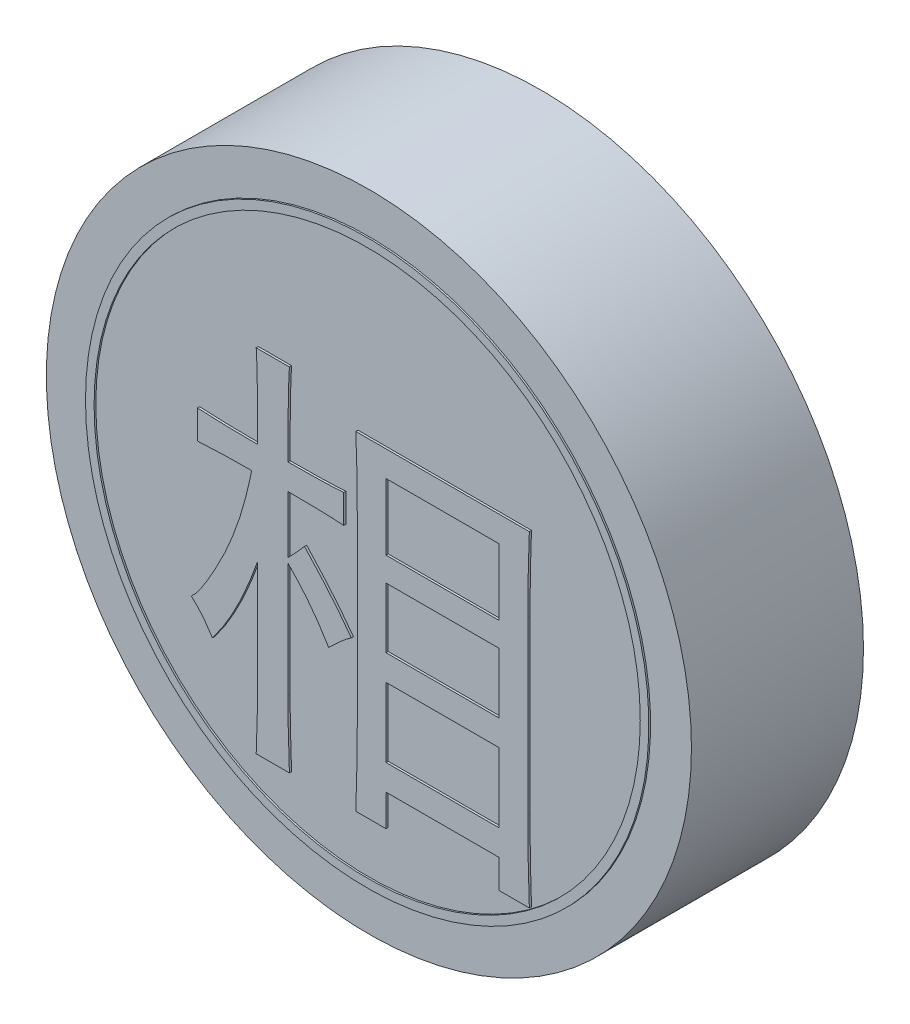
SolidWorks part; units mm, degrees
ref_plane "前视基准面" through (0, 0, 0) normal (0, 0, 1) x (1, 0, 0)
ref_plane "上视基准面" through (0, 0, 0) normal (0, 1, 0) x (1, 0, 0)
ref_plane "右视基准面" through (0, 0, 0) normal (1, 0, 0) x (0, 0, -1)
other "Configuration Table"
sketch "草图1" plane through (0, 0, 0) normal (0, 0, 1) x (1, 0, 0)
  circle A0 centre (0, 0) radius 15
  dimension "D1" = 30
extrude "Diameter30_Height8" add sketch "草图1" against normal blind 8
sketch "草图2" plane through (0, 0, 0) normal (0, 0, 1) x (1, 0, 0)
  text T0 "相" font "SimHei" height 12
extrude "Character_相" add sketch "草图2" along normal blind 0.1
sketch "草图3" plane through (0, 0, 0) normal (0, 0, 1) x (1, 0, 0)
  circle A0 centre (0, 0) radius 13.1
  circle A1 centre (0, 0) radius 12.7
extrude "Ink_ring" add sketch "草图3" along normal blind 0.08
